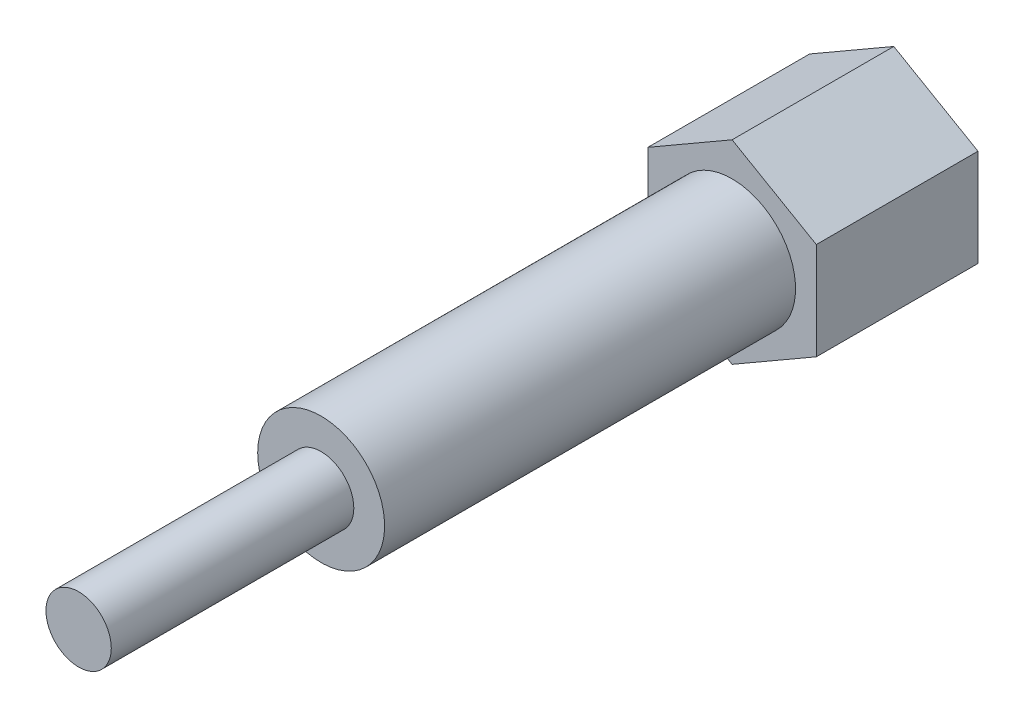
SolidWorks part; units mm, degrees
ref_plane "Alzado" through (0, 0, 0) normal (0, 0, 1) x (1, 0, 0)
ref_plane "Planta" through (0, 0, 0) normal (0, 1, 0) x (1, 0, 0)
ref_plane "Vista lateral" through (0, 0, 0) normal (1, 0, 0) x (0, 0, -1)
sketch "Croquis1" plane through (0, 0, 0) normal (0, 0, 1) x (1, 0, 0)
  line L0 (0, 0) -> (0, 7.2169) construction
  line L2 (0, 7.2169) -> (-6.25, 3.6084)
  line L3 (-6.25, 3.6084) -> (-6.25, -3.6084)
  line L4 (-6.25, -3.6084) -> (0, -7.2169)
  line L5 (0, -7.2169) -> (6.25, -3.6084)
  line L6 (6.25, -3.6084) -> (6.25, 3.6084)
  line L7 (6.25, 3.6084) -> (0, 7.2169)
  circle A0 centre (0, 0) radius 6.25 construction
  dimension "D1" = 12.5
extrude "Saliente-Extruir1" add sketch "Croquis1" along normal blind 12
sketch "Croquis2" plane through (0, 0, 12) normal (0, 0, 1) x (1, 0, 0)
  circle A0 centre (0, 0) radius 4.71
  dimension "D1" = 9.42
extrude "Saliente-Extruir2" add sketch "Croquis2" along normal blind 30.5
sketch "Croquis3" plane through (0, 0, 42.5) normal (0, 0, 1) x (1, 0, 0)
  circle A0 centre (0, 0) radius 2.425
  dimension "D1" = 4.85
extrude "Saliente-Extruir3" add sketch "Croquis3" along normal blind 18
